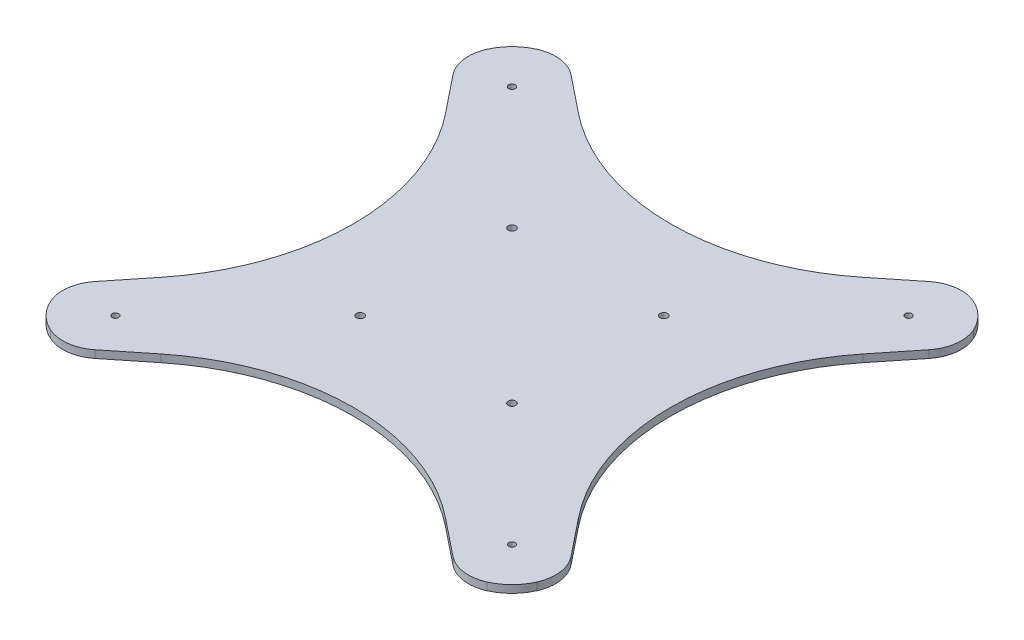
SolidWorks part; units mm, degrees
ref_plane "Спереди" through (0, 0, 0) normal (0, 0, 1) x (1, 0, 0)
ref_plane "Сверху" through (0, 0, 0) normal (0, 1, 0) x (1, 0, 0)
ref_plane "Справа" through (0, 0, 0) normal (1, 0, 0) x (0, 0, -1)
sketch "Эскиз5" plane through (0, 0, 0) normal (0, 1, 0) x (1, 0, 0)
  line L0 (-100, 130) -> (-74.9634, 109.9707)
  line L7 (74.9634, 109.9707) -> (100, 130)
  line L8 (-130, 100) -> (-109.9707, 74.9634)
  line L9 (-109.9707, -74.9634) -> (-130, -100)
  line L10 (-100, -130) -> (-74.9634, -109.9707)
  line L11 (74.9634, -109.9707) -> (100, -130)
  line L12 (130, 100) -> (109.9707, 74.9634)
  line L13 (109.9707, -74.9634) -> (130, -100)
  arc A0 (74.9634, 109.9707) -> (-74.9634, 109.9707) centre (0, 203.675) cw
  arc A1 (-109.9707, 74.9634) -> (-109.9707, -74.9634) centre (-203.675, 0) cw
  arc A2 (-74.9634, -109.9707) -> (74.9634, -109.9707) centre (0, -203.675) cw
  arc A3 (109.9707, 74.9634) -> (109.9707, -74.9634) centre (203.675, 0) ccw
  arc A4 (-100, 130) -> (-130, 100) centre (-104.5, 104.5) ccw
  arc A5 (130, 100) -> (100, 130) centre (104.5, 104.5) ccw
  arc A6 (100, -130) -> (130, -100) centre (104.5, -104.5) ccw
  arc A7 (-130, -100) -> (-100, -130) centre (-104.5, -104.5) ccw
  circle A8 centre (-104.5, -104.5) radius 1.75
  circle A9 centre (-104.5, 104.5) radius 1.75
  circle A10 centre (104.5, 104.5) radius 1.75
  circle A11 centre (104.5, -104.5) radius 1.75
  point P0 (0, 0)
  point P28 (0, 50)
  point P31 (-50, 0)
  point P34 (0, -50)
  point P37 (50, 0)
  dimension "D2" = 120
  dimension "D1" = 3.5
  dimension "D3" = 3.5
  dimension "D4" = 3.5
  dimension "D5" = 3.5
extrude "Бобышка-Вытянуть3" add sketch "Эскиз5" along normal blind 4 contours A2 L11 A6 L13 A3 L12 A5 L7 A0 L0 A4 L8 A1 L9 A7 L10
fillet "Скругление3" radius 20 1 edges at (130, 2, -100)
fillet "Скругление4" radius 20 1 edges at (100, 2, -130)
fillet "Скругление5" radius 20 1 edges at (-100, 2, -130)
fillet "Скругление6" radius 20 1 edges at (-130, 2, -100)
fillet "Скругление7" radius 20 1 edges at (-100, 2, 130)
fillet "Скругление8" radius 20 1 edges at (-130, 2, 100)
fillet "Скругление9" radius 20 1 edges at (100, 2, 130)
fillet "Скругление10" radius 20 1 edges at (130, 2, 100)
sketch "Эскиз6" plane through (0, 4, 0) normal (0, 1, 0) x (1, 0, 0)
  circle A0 centre (-104.5, 104.5) radius 1.75
  circle A1 centre (104.5, 104.5) radius 1.75
  circle A2 centre (104.5, -104.5) radius 1.75
  circle A3 centre (-104.5, -104.5) radius 1.75
  point P0 (0, 0)
  dimension "D2" = 3.5
  dimension "D3" = 3.5
  dimension "D4" = 3.5
  dimension "D5" = 3.5
  dimension "D1" = 209
extrude "Вырез-Вытянуть3" cut sketch "Эскиз6" against normal blind 4
sketch "Эскиз7" plane through (0, 4, 0) normal (0, 1, 0) x (1, 0, 0)
  circle A0 centre (-40, 40) radius 2
  circle A1 centre (40, 40) radius 2
  circle A2 centre (40, -40) radius 2
  circle A3 centre (-40, -40) radius 2
  point P0 (0, 0)
  dimension "D2" = 4
  dimension "D3" = 4
  dimension "D4" = 4
  dimension "D5" = 4
  dimension "D1" = 80
extrude "Вырез-Вытянуть4" cut sketch "Эскиз7" against normal blind 4
